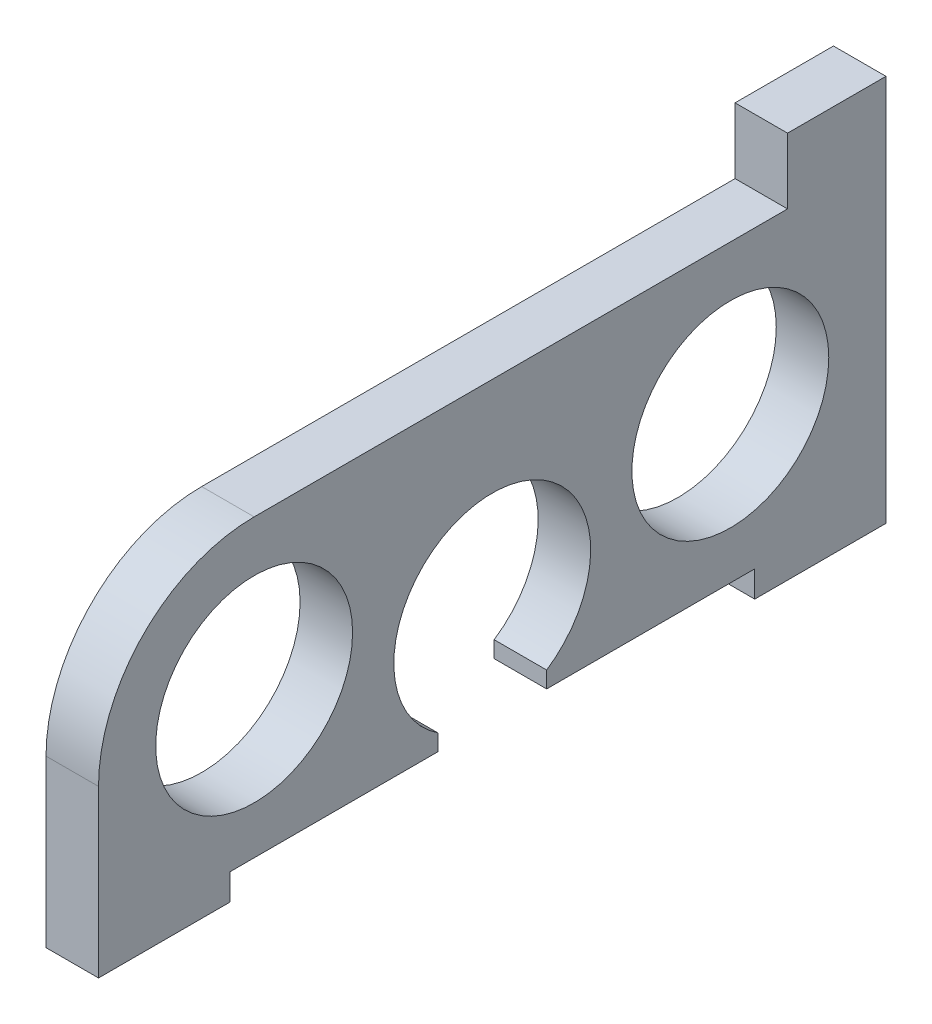
SolidWorks part; units mm, degrees
ref_plane "정면" through (0, 0, 0) normal (0, 0, 1) x (1, 0, 0)
ref_plane "윗면" through (0, 0, 0) normal (0, 1, 0) x (1, 0, 0)
ref_plane "우측면" through (0, 0, 0) normal (1, 0, 0) x (0, 0, -1)
sketch "스케치1" plane through (0, 0, 0) normal (1, 0, 0) x (0, 0, -1)
  line L0 (-9.5123, 0) -> (14.4726, 0) construction
  line L1 (-7.2565, 1.8) -> (-7.2565, 1)
  line L2 (-24.2092, 1.8) -> (25.0232, 1.8)
  line L3 (-24.2092, 1.8) -> (-24.2092, 1)
  line L4 (-24.2092, 1) -> (25.0232, 1)
  line L5 (25.0232, 1.8) -> (25.0232, 1)
  line L10 (7.2565, 1.8) -> (7.2565, 1)
  line L11 (11.8565, 1.8) -> (11.8565, 1)
  line L12 (-11.8565, 1.8) -> (-11.8565, 1)
  line L13 (-7.2565, 6.25) -> (0, 4.8) construction
  line L14 (0, 4.8) -> (7.2565, 6.25) construction
  circle A0 centre (-7.2565, 6.25) radius 6.25
  circle A1 centre (7.2565, 6.25) radius 6.25
  circle A2 centre (0, 4.8) radius 1.8
  circle A3 centre (0, 4.8) radius 3
  circle A4 centre (-7.2565, 6.25) radius 5.4
  circle A5 centre (7.2565, 6.25) radius 5.4
  circle A6 centre (19.8088, 4.2) radius 2.4
  circle A7 centre (19.8088, 4.2) radius 2.95
  circle A8 centre (-7.2565, 6.25) radius 3
  circle A9 centre (7.2565, 6.25) radius 3
  circle A10 centre (-1.8632, 5.1723) radius 0.1
  point P23 (21.5242, 1.8)
  point P24 (18.0934, 1.8)
  point P31 (-8.8014, 6.25)
  point P32 (-7.1823, 6.25)
  point P35 (-7.2511, 6.25)
  point P36 (0, 0)
  dimension "D1" = 12.5
  dimension "D2" = 3.6
  dimension "D3" = 6
  dimension "D4" = 10.8
  dimension "D11" = 5.9
  dimension "D12" = 4.8
  dimension "D14" = 6
  dimension "D15" = 6
  dimension "D5" = 0.2
  dimension "D7" = 0.8
  dimension "D8" = 4.6
  dimension "D9" = 4.6
  dimension "D10" = 1
sketch "스케치2" plane through (0, 0, 0) normal (1, 0, 0) x (0, 0, -1)
  line L1 (-24.2092, 1) -> (25.0232, 1) construction
  line L6 (12, 1) -> (8, 1)
  line L19 (1.6583, 2.3) -> (1.6583, 1.8)
  line L20 (-24.2092, 1.8) -> (25.0232, 1.8) construction
  line L21 (8, 1) -> (8, 1.8)
  line L22 (-1.6583, 2.3) -> (-1.6583, 1.8)
  line L23 (-1.6583, 1.8) -> (-8, 1.8)
  line L24 (12, 1) -> (12, 12.8)
  line L25 (8, 1.8) -> (1.6583, 1.8)
  line L26 (-8, 1.8) -> (-8, 1)
  line L27 (-8, 1) -> (-12, 1)
  line L28 (-12, 1) -> (-12, 6.0565)
  line L29 (-7.2565, 10.8) -> (9, 10.8)
  line L30 (9, 10.8) -> (9, 12.8)
  line L31 (9, 12.8) -> (12, 12.8)
  arc A2 (-7.2565, 10.8) -> (-12, 6.0565) centre (-7.2565, 6.0565) ccw
  circle A4 centre (-7.2565, 6.25) radius 3 construction
  circle A6 centre (-7.2565, 6.25) radius 3
  circle A7 centre (7.2565, 6.25) radius 3 construction
  circle A10 centre (7.2565, 6.25) radius 3
  arc A13 (-1.6583, 2.3) -> (1.6583, 2.3) centre (0, 4.8) cw
  circle A14 centre (0, 4.8) radius 3 construction
  point P10 (-12, 5.3515)
  point P29 (-7.2565, 6.0565)
  dimension "D1" = 0.5
  dimension "D5" = 9
  dimension "D2" = 12
  dimension "D3" = 4
  dimension "D4" = 12
  dimension "D6" = 4
  dimension "D7" = 2
  dimension "D8" = 3
extrude "보스-돌출1" add sketch "스케치2" along normal blind 1.6 contours L30 L31 L24 L6 L21 L25 L19 A13 L22 L23 L26 L27 L28 A2 L29 | A6 | A10
